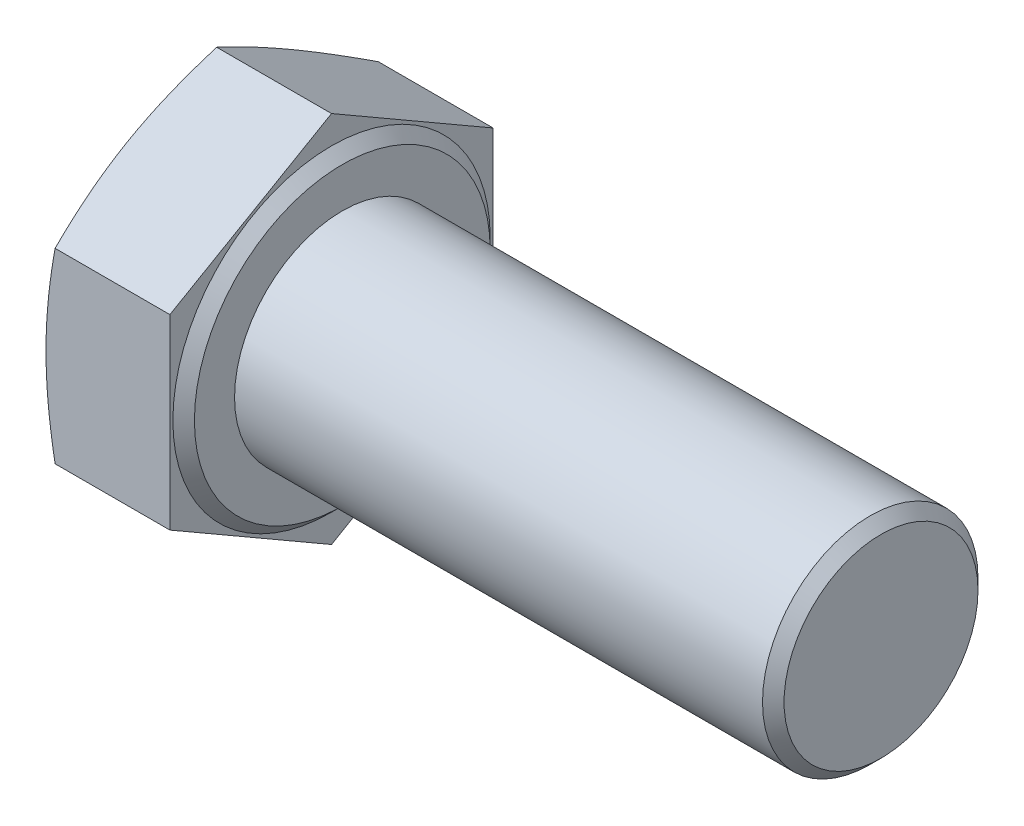
SolidWorks part; units mm, degrees
ref_plane "Front" through (0, 0, 0) normal (0, 0, 1) x (1, 0, 0)
ref_plane "Top" through (0, 0, 0) normal (0, 1, 0) x (1, 0, 0)
ref_plane "Right" through (0, 0, 0) normal (1, 0, 0) x (0, 0, -1)
other "Configuration Table"
sketch "Sketch2" plane through (0, 0, 0) normal (1, 0, 0) x (0, 0, -1)
  line L1 (0, -10.3923) -> (9, -5.1962)
  line L2 (9, -5.1962) -> (9, 5.1962)
  line L3 (9, 5.1962) -> (0, 10.3923)
  line L4 (0, 10.3923) -> (-9, 5.1962)
  line L5 (-9, 5.1962) -> (-9, -5.1962)
  line L6 (-9, -5.1962) -> (0, -10.3923)
  circle A0 centre (0, 0) radius 9 construction
  dimension "s" = 18
extrude "BaseHead" add sketch "Sketch2" along normal blind 7.5
sketch "Sketch3" plane through (0, 0, 0) normal (0, 0, 1) x (1, 0, 0)
  line L0 (7.5, 10.3923) -> (7.5, 8.235)
  line L2 (7.5, 8.235) -> (6.9, 8.835)
  line L3 (6.9, 8.835) -> (6.9, 10.3923)
  line L5 (6.9, 10.3923) -> (7.5, 10.3923)
  line L6 (-0.9571, 0) -> (7.6478, 0) construction
  line L7 (7.5, 10.3923) -> (0, 10.3923) construction
  dimension "D1" = 45
  dimension "c" = 0.6
  dimension "dw" = 16.47
revolve "BearingFace" cut sketch "Sketch3" angle 360 about L6
sketch "Sketch4" plane through (0, 0, 0) normal (0, 0, 1) x (1, 0, 0)
  line L0 (-0.4935, 0) -> (3.5626, 0) construction
  line L2 (0, 10.3923) -> (0.5068, 10.3923)
  line L4 (0.5068, 10.3923) -> (0, 9)
  line L6 (0, 9) -> (0, 10.3923)
  line L7 (6.9, 10.3923) -> (0, 10.3923) construction
  dimension "D1" = 20
  dimension "D2" = 18
revolve "HeadChamfer" cut sketch "Sketch4" angle 360 about L0
sketch "Sketch5" plane through (7.5, 0, 0) normal (1, 0, 0) x (0, 0, -1)
  circle A0 centre (0, 0) radius 6
  dimension "d" = 12
extrude "BaseBody" add sketch "Sketch5" along normal blind 30
cosmetic thread "ThreadCosmetic1" [suppressed] parameters "D2"=10.106
chamfer "Chamfer1" distance 0.6 angle 45 1 edges at (37.5, 0, -6)
fillet "HeadFillet" [suppressed] radius 0.6
sketch "Sketch6" plane through (0, 0, 0) normal (0, 0, 1) x (1, 0, 0)
  line L0 (7.5, 6.947) -> (8.447, 6.947)
  line L1 (8.447, 6.947) -> (8.447, 6)
  line L2 (8.447, 6) -> (7.9735, 5.1799)
  line L3 (7.9735, 5.1799) -> (7.5, 6)
  line L4 (7.5, 6) -> (7.5, 6.947)
  line L5 (7.5, -8.235) -> (7.5, 8.235) construction
  line L6 (36.9, 6) -> (7.5, 6) construction
  dimension "D1" = 0.947
revolve "Cut-Revolve10" [suppressed] cut sketch "Sketch6" angle 360
pattern_linear "LPattern10" [suppressed] count 26
equation "\"D2@Sketch4\" = \"s@Sketch2\""
equation "\"D1@Chamfer1\" = 0.05 * \"d@Sketch5\""
equation "\"D1@Sketch6\" =  ( \"d@Sketch5\" - \"D2@ThreadCosmetic1\" )  / 2"
equation "\"pitch@LPattern10\" = 1.2 * \"D1@Sketch6\""
equation "\"D1@LPattern10\" = (  \"l@BaseBody\"-\"D1@Chamfer1\" )  / \"pitch@LPattern10\""
